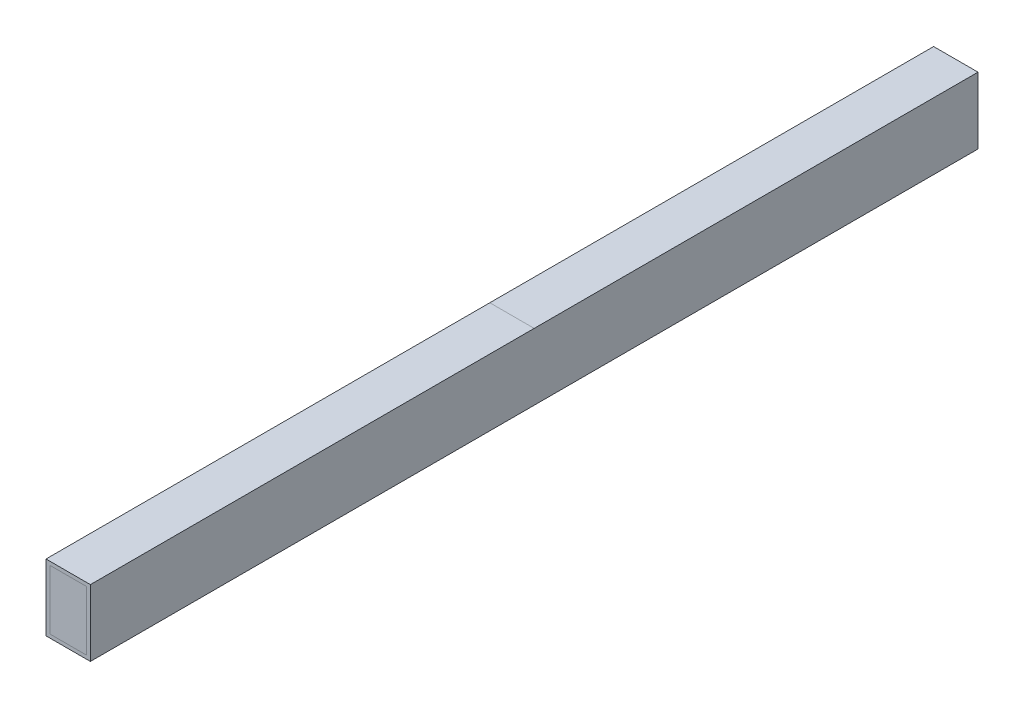
SolidWorks part; units mm, degrees
ref_plane "Płaszczyzna przednia" through (0, 0, 0) normal (0, 0, 1) x (1, 0, 0)
ref_plane "Płaszczyzna górna" through (0, 0, 0) normal (0, 1, 0) x (1, 0, 0)
ref_plane "Płaszczyzna prawa" through (0, 0, 0) normal (1, 0, 0) x (0, 0, -1)
sketch "Szkic1" plane through (0, 0, 0) normal (0, 0, 1) x (1, 0, 0)
  line L1 (0, 0) -> (10, 0)
  line L2 (0, 0) -> (0, -15)
  line L3 (0, -15) -> (10, -15)
  line L4 (10, 0) -> (10, -15)
  dimension "D1" = 10
  dimension "D2" = 15
extrude "Dodanie-wyciągnięcie3" add sketch "Szkic1" along normal blind 200
sketch "Szkic2" plane through (0, 0, 0) normal (0, 1, 0) x (1, 0, 0)
  line L0 (0, -100) -> (10, -100)
  line L1 (0, -200) -> (0, 0) construction
  line L2 (10, -200) -> (10, 0) construction
split line "Linia podziałowa1"
sketch "Szkic3" plane through (0, 0, 200) normal (0, 0, 1) x (1, 0, 0)
  line L0 (10, 0) -> (0, 0) construction
  line L1 (0.9, -0.8) -> (9.1, -0.8)
  line L2 (0.9, -0.8) -> (0.9, -14.2)
  line L3 (0.9, -14.2) -> (9.1, -14.2)
  line L4 (9.1, -0.8) -> (9.1, -14.2)
  line L5 (0, -15) -> (10, -15) construction
  line L6 (0, 0) -> (0, -15) construction
  line L7 (10, -15) -> (10, 0) construction
  dimension "D1" = 0.8
  dimension "D2" = 0.8
  dimension "D3" = 0.9
  dimension "D4" = 0.9
split "Podziel1" trim tools "Szkic3" bodies to split 104 resulting bodies 105 106
sketch "Szkic4" plane through (0, 0, 0) normal (0, 1, 0) x (1, 0, 0)
  line L0 (0, -199.1) -> (10, -199.1)
  line L1 (0, -200) -> (0, -100) construction
  line L2 (10, -200) -> (10, -100) construction
  line L3 (0.9, -200) -> (9.1, -200) construction
  dimension "D1" = 0.9
